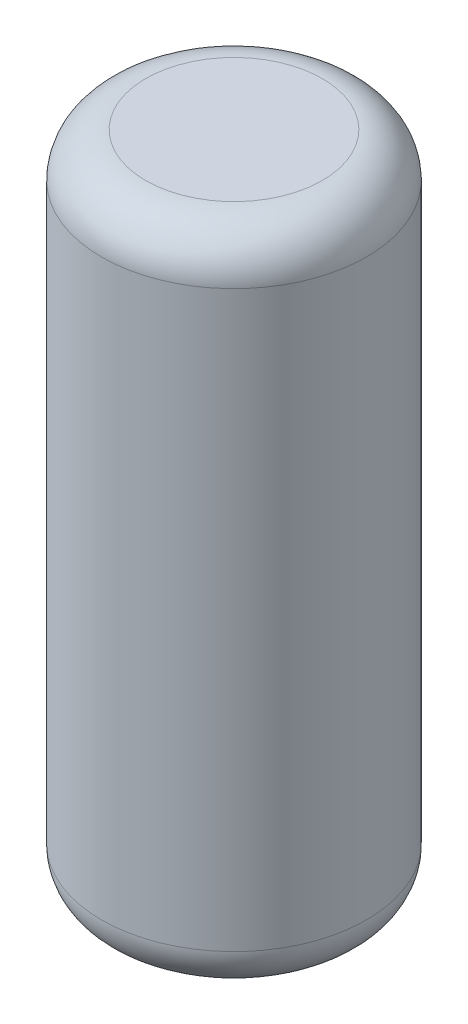
SolidWorks part; units mm, degrees
material "Oak"
ref_plane "Front Plane" through (0, 0, 0) normal (0, 0, 1) x (1, 0, 0)
ref_plane "Top Plane" through (0, 0, 0) normal (0, 1, 0) x (1, 0, 0)
ref_plane "Right Plane" through (0, 0, 0) normal (1, 0, 0) x (0, 0, -1)
sketch "Sketch1" plane through (0, 0, 0) normal (0, 1, 0) x (1, 0, 0)
  circle A0 centre (0, 0) radius 3.81
  dimension "D1" = 7.62
extrude "Boss-Extrude1" add sketch "Sketch1" along normal mid plane 19.05
fillet "Fillet1" radius 1.27 2 edges at (0, -9.525, 3.81) (0, 9.525, 3.81)
